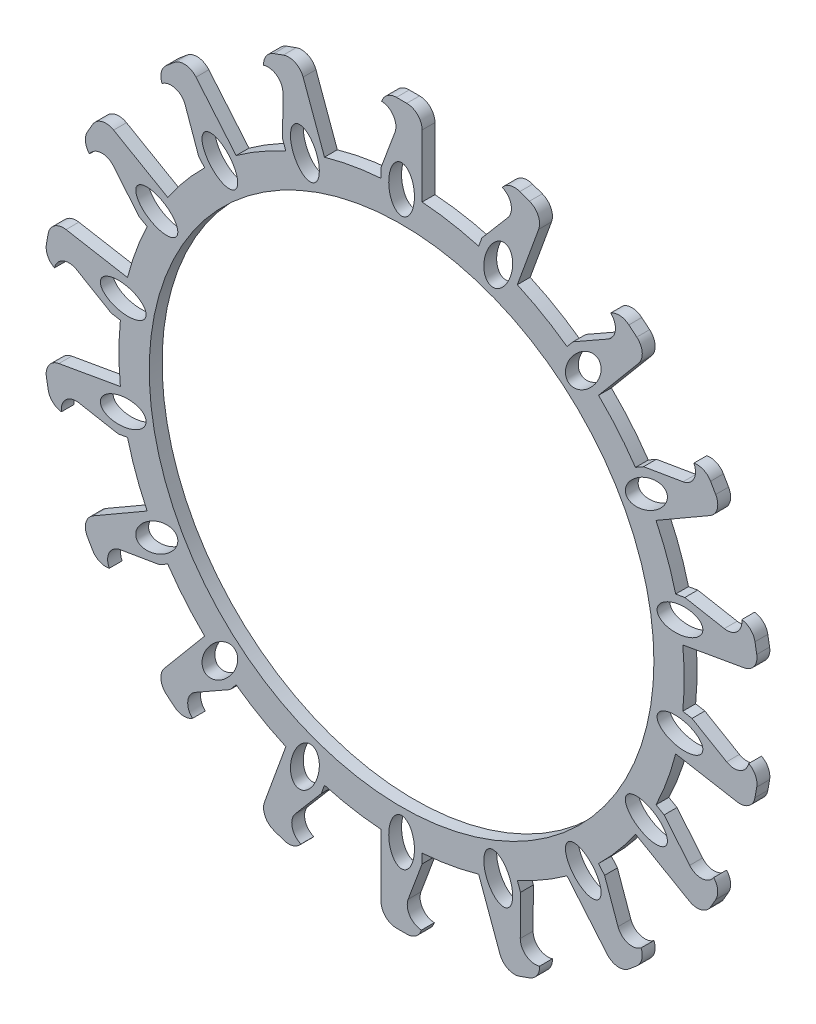
SolidWorks part; units mm, degrees
ref_plane "Front Plane" through (0, 0, 0) normal (0, 0, 1) x (1, 0, 0)
ref_plane "Top Plane" through (0, 0, 0) normal (0, 1, 0) x (1, 0, 0)
ref_plane "Right Plane" through (0, 0, 0) normal (1, 0, 0) x (0, 0, -1)
sketch "Sketch1" plane through (0, 0, 0) normal (0, 0, 1) x (1, 0, 0)
  line L0 (-78.3987, -3.3654) -> (61.3013, -3.3654) construction
  line L1 (-5.8227, 60.5836) -> (-5.8227, 59.1774)
  line L2 (-57.9401, 46.026) -> (40.8427, -52.7569) construction
  line L3 (40.8427, 46.026) -> (-57.9401, -52.7569) construction
  line L4 (-13.4427, 60.5073) -> (-13.4427, 59.1774)
  line L5 (-13.4427, 59.1774) -> (-5.8227, 59.1774)
  line L12 (2.7798, 58.212) -> (10.1401, 56.2398)
  line L13 (10.5041, 57.5981) -> (10.1401, 56.2398)
  line L14 (3.124, 59.4967) -> (2.7798, 58.212)
  line L18 (18.1997, 53.0809) -> (24.7988, 49.2709)
  line L19 (25.5019, 50.4887) -> (24.7988, 49.2709)
  line L20 (18.8647, 54.2327) -> (18.1997, 53.0809)
  line L24 (31.7661, 44.1336) -> (37.1543, 38.7454)
  line L25 (38.1486, 39.7398) -> (37.1543, 38.7454)
  line L26 (32.7065, 45.074) -> (31.7661, 44.1336)
  line L30 (42.5546, 31.9799) -> (46.3646, 25.3808)
  line L31 (47.5824, 26.0839) -> (46.3646, 25.3808)
  line L32 (43.7063, 32.6449) -> (42.5546, 31.9799)
  line L36 (49.8298, 17.4482) -> (51.802, 10.0878)
  line L37 (53.1603, 10.4518) -> (51.802, 10.0878)
  line L38 (51.1145, 17.7924) -> (49.8298, 17.4482)
  line L42 (53.0961, 1.5286) -> (53.0961, -6.0914)
  line L43 (54.5023, -6.0914) -> (53.0961, -6.0914)
  line L44 (54.426, 1.5286) -> (53.0961, 1.5286)
  line L48 (52.1307, -14.6939) -> (50.1585, -22.0543)
  line L49 (51.5168, -22.4183) -> (50.1585, -22.0543)
  line L50 (53.4154, -15.0382) -> (52.1307, -14.6939)
  line L54 (46.9996, -30.1138) -> (43.1896, -36.713)
  line L55 (44.4074, -37.4161) -> (43.1896, -36.713)
  line L56 (48.1513, -30.7788) -> (46.9996, -30.1138)
  line L60 (38.0523, -43.6803) -> (32.6641, -49.0684)
  line L61 (33.6585, -50.0628) -> (32.6641, -49.0684)
  line L62 (38.9927, -44.6207) -> (38.0523, -43.6803)
  line L66 (25.8986, -54.4687) -> (19.2995, -58.2787)
  line L67 (20.0026, -59.4965) -> (19.2995, -58.2787)
  line L68 (26.5636, -55.6205) -> (25.8986, -54.4687)
  line L72 (11.3669, -61.744) -> (4.0065, -63.7162)
  line L73 (4.3705, -65.0745) -> (4.0065, -63.7162)
  line L74 (11.7111, -63.0286) -> (11.3669, -61.744)
  line L78 (-4.5527, -65.0102) -> (-12.1727, -65.0102)
  line L79 (-12.1727, -66.4164) -> (-12.1727, -65.0102)
  line L80 (-4.5527, -66.3402) -> (-4.5527, -65.0102)
  line L84 (-20.7752, -64.0449) -> (-28.1356, -62.0727)
  line L85 (-28.4996, -63.431) -> (-28.1356, -62.0727)
  line L86 (-21.1195, -65.3295) -> (-20.7752, -64.0449)
  line L90 (-36.1951, -58.9137) -> (-42.7943, -55.1037)
  line L91 (-43.4974, -56.3215) -> (-42.7943, -55.1037)
  line L92 (-36.8601, -60.0655) -> (-36.1951, -58.9137)
  line L96 (-49.7616, -49.9665) -> (-55.1497, -44.5783)
  line L97 (-56.1441, -45.5726) -> (-55.1497, -44.5783)
  line L98 (-50.702, -50.9069) -> (-49.7616, -49.9665)
  line L102 (-60.55, -37.8128) -> (-64.36, -31.2137)
  line L103 (-65.5778, -31.9168) -> (-64.36, -31.2137)
  line L104 (-61.7018, -38.4778) -> (-60.55, -37.8128)
  line L109 (-71.1558, -16.2846) -> (-69.7975, -15.9207)
  line L110 (-69.1099, -23.6252) -> (-67.8253, -23.281)
  line L114 (-71.0915, -7.3614) -> (-71.0915, 0.2586)
  line L115 (-72.4977, 0.2586) -> (-71.0915, 0.2586)
  line L116 (-72.4215, -7.3614) -> (-71.0915, -7.3614)
  line L120 (-70.1262, 8.8611) -> (-68.154, 16.2214)
  line L121 (-69.5123, 16.5854) -> (-68.154, 16.2214)
  line L122 (-71.4108, 9.2053) -> (-70.1262, 8.8611)
  line L126 (-64.995, 24.281) -> (-61.185, 30.8801)
  line L127 (-62.4028, 31.5832) -> (-61.185, 30.8801)
  line L128 (-66.1468, 24.946) -> (-64.995, 24.281)
  line L132 (-56.0478, 37.8474) -> (-50.6596, 43.2356)
  line L133 (-51.6539, 44.2299) -> (-50.6596, 43.2356)
  line L134 (-56.9882, 38.7878) -> (-56.0478, 37.8474)
  line L138 (-43.8941, 48.6359) -> (-37.295, 52.4459)
  line L139 (-37.9981, 53.6637) -> (-37.295, 52.4459)
  line L140 (-44.5591, 49.7877) -> (-43.8941, 48.6359)
  line L144 (-29.3623, 55.9111) -> (-22.002, 57.8833)
  line L145 (-22.3659, 59.2416) -> (-22.002, 57.8833)
  line L146 (-29.7065, 57.1958) -> (-29.3623, 55.9111)
  line L147 (-8.9977, -2.9164) -> (-5.8227, 59.1774) construction
  line L148 (-8.9977, -2.9164) -> (10.1401, 56.2398) construction
  line L170 (-67.8253, -23.281) -> (-69.7975, -15.9207) [skipped]
  circle A0 centre (-8.5487, -3.3654) radius 55.245
  circle A1 centre (-8.5487, -3.3654) radius 69.85
  dimension "D1" = 110.49
  dimension "D2" = 139.7
  dimension "D4" = 7.62
  dimension "D5" = 24
  dimension "D6" = 15
extrude "Boss-Extrude1" add sketch "Sketch1" along normal blind 3.175
sketch "Sketch2" plane through (0, 0, 3.175) normal (0, 0, -1) x (-1, 0, 0)
  line L0 (8.5487, 66.4846) -> (8.5487, -73.2154) construction
  line L1 (8.5487, 62.6746) -> (13.6287, 62.6746)
  line L2 (8.5487, 62.6746) -> (3.4687, 62.6746)
  line L3 (3.4687, 62.6746) -> (3.4687, 85.5346)
  line L4 (3.4687, 85.5346) -> (13.6287, 85.5346)
  line L5 (13.6287, 85.5346) -> (13.6287, 62.6746)
  line L6 (8.5487, -3.3654) -> (-61.3013, -3.3654) construction
  line L7 (34.1807, 81.9107) -> (43.7279, 78.4358)
  line L8 (43.7279, 78.4358) -> (35.9094, 56.9544)
  line L9 (26.3621, 60.4293) -> (34.1807, 81.9107)
  line L10 (31.1357, 58.6919) -> (26.3621, 60.4293)
  line L11 (31.1357, 58.6919) -> (35.9094, 56.9544)
  line L12 (61.801, 68.0013) -> (69.584, 61.4705)
  line L13 (69.584, 61.4705) -> (54.8899, 43.9588)
  line L14 (47.1069, 50.4895) -> (61.801, 68.0013)
  line L15 (50.9984, 47.2241) -> (47.1069, 50.4895)
  line L16 (50.9984, 47.2241) -> (54.8899, 43.9588)
  line L17 (82.9984, 45.484) -> (88.0784, 36.6851)
  line L18 (88.0784, 36.6851) -> (68.281, 25.2551)
  line L19 (63.201, 34.054) -> (82.9984, 45.484)
  line L20 (65.741, 29.6546) -> (63.201, 34.054)
  line L21 (65.741, 29.6546) -> (68.281, 25.2551)
  line L22 (95.216, 17.0747) -> (96.9803, 7.0691)
  line L23 (96.9803, 7.0691) -> (74.4676, 3.0995)
  line L24 (72.7033, 13.1051) -> (95.216, 17.0747)
  line L25 (73.5854, 8.1023) -> (72.7033, 13.1051)
  line L26 (73.5854, 8.1023) -> (74.4676, 3.0995)
  line L27 (96.9803, -13.7999) -> (95.216, -23.8056)
  line L28 (95.216, -23.8056) -> (72.7033, -19.836)
  line L29 (74.4676, -9.8303) -> (96.9803, -13.7999)
  line L30 (73.5854, -14.8332) -> (74.4676, -9.8303)
  line L31 (73.5854, -14.8332) -> (72.7033, -19.836)
  line L32 (88.0784, -43.416) -> (82.9984, -52.2149)
  line L33 (82.9984, -52.2149) -> (63.201, -40.7849)
  line L34 (68.281, -31.986) -> (88.0784, -43.416)
  line L35 (65.741, -36.3854) -> (68.281, -31.986)
  line L36 (65.741, -36.3854) -> (63.201, -40.7849)
  line L37 (69.584, -68.2014) -> (61.801, -74.7322)
  line L38 (61.801, -74.7322) -> (47.1069, -57.2204)
  line L39 (54.8899, -50.6897) -> (69.584, -68.2014)
  line L40 (50.9984, -53.955) -> (54.8899, -50.6897)
  line L41 (50.9984, -53.955) -> (47.1069, -57.2204)
  line L42 (43.7279, -85.1667) -> (34.1807, -88.6416)
  line L43 (34.1807, -88.6416) -> (26.3621, -67.1602)
  line L44 (35.9094, -63.6853) -> (43.7279, -85.1667)
  line L45 (31.1357, -65.4227) -> (35.9094, -63.6853)
  line L46 (31.1357, -65.4227) -> (26.3621, -67.1602)
  line L47 (13.6287, -92.2654) -> (3.4687, -92.2654)
  line L48 (3.4687, -92.2654) -> (3.4687, -69.4054)
  line L49 (13.6287, -69.4054) -> (13.6287, -92.2654)
  line L50 (8.5487, -69.4054) -> (13.6287, -69.4054)
  line L51 (8.5487, -69.4054) -> (3.4687, -69.4054)
  line L52 (-17.0832, -88.6416) -> (-26.6305, -85.1667)
  line L53 (-26.6305, -85.1667) -> (-18.8119, -63.6853)
  line L54 (-9.2647, -67.1602) -> (-17.0832, -88.6416)
  line L55 (-14.0383, -65.4227) -> (-9.2647, -67.1602)
  line L56 (-14.0383, -65.4227) -> (-18.8119, -63.6853)
  line L57 (-44.7036, -74.7322) -> (-52.4866, -68.2014)
  line L58 (-52.4866, -68.2014) -> (-37.7925, -50.6897)
  line L59 (-30.0095, -57.2204) -> (-44.7036, -74.7322)
  line L60 (-33.901, -53.955) -> (-30.0095, -57.2204)
  line L61 (-33.901, -53.955) -> (-37.7925, -50.6897)
  line L62 (-65.9009, -52.2149) -> (-70.9809, -43.416)
  line L63 (-70.9809, -43.416) -> (-51.1836, -31.986)
  line L64 (-46.1036, -40.7849) -> (-65.9009, -52.2149)
  line L65 (-48.6436, -36.3854) -> (-46.1036, -40.7849)
  line L66 (-48.6436, -36.3854) -> (-51.1836, -31.986)
  line L67 (-78.1186, -23.8056) -> (-79.8828, -13.7999)
  line L68 (-79.8828, -13.7999) -> (-57.3701, -9.8303)
  line L69 (-55.6059, -19.836) -> (-78.1186, -23.8056)
  line L70 (-56.488, -14.8332) -> (-55.6059, -19.836)
  line L71 (-56.488, -14.8332) -> (-57.3701, -9.8303)
  line L72 (-79.8828, 7.0691) -> (-78.1186, 17.0747)
  line L73 (-78.1186, 17.0747) -> (-55.6059, 13.1051)
  line L74 (-57.3701, 3.0995) -> (-79.8828, 7.0691)
  line L75 (-56.488, 8.1023) -> (-57.3701, 3.0995)
  line L76 (-56.488, 8.1023) -> (-55.6059, 13.1051)
  line L77 (-70.9809, 36.6851) -> (-65.9009, 45.484)
  line L78 (-65.9009, 45.484) -> (-46.1036, 34.054)
  line L79 (-51.1836, 25.2551) -> (-70.9809, 36.6851)
  line L80 (-48.6436, 29.6546) -> (-51.1836, 25.2551)
  line L81 (-48.6436, 29.6546) -> (-46.1036, 34.054)
  line L82 (-52.4866, 61.4705) -> (-44.7036, 68.0013)
  line L83 (-44.7036, 68.0013) -> (-30.0095, 50.4895)
  line L84 (-37.7925, 43.9588) -> (-52.4866, 61.4705)
  line L85 (-33.901, 47.2241) -> (-37.7925, 43.9588)
  line L86 (-33.901, 47.2241) -> (-30.0095, 50.4895)
  line L87 (-26.6305, 78.4358) -> (-17.0832, 81.9107)
  line L88 (-17.0832, 81.9107) -> (-9.2647, 60.4293)
  line L89 (-18.8119, 56.9544) -> (-26.6305, 78.4358)
  line L90 (-14.0383, 58.6919) -> (-18.8119, 56.9544)
  line L91 (-14.0383, 58.6919) -> (-9.2647, 60.4293)
  circle A2 centre (8.5487, -3.3654) radius 69.85 construction
  point P99 (8.5487, -3.3654)
  dimension "D3" = 3.81
  dimension "D1" = 5.08
  dimension "D2" = 5.08
  dimension "D4" = 22.86
  dimension "D5" = 18
extrude "Boss-Extrude2" add sketch "Sketch2" along normal blind 3.175
fillet "Fillet4" radius 3.81 36 edges at (-13.6287, 85.5346, 1.5875) (-3.4687, 85.5346, 1.5875) (-88.0784, 36.6851, 1.5875) (-82.9984, 45.484, 1.5875) (-95.216, 17.0747, 1.5875) (-96.9803, 7.0691, 1.5875) (-96.9803, -13.7999, 1.5875) (-95.216, -23.8056, 1.5875) (-88.0784, -43.416, 1.5875) (-82.9984, -52.2149, 1.5875) (-69.584, -68.2014, 1.5875) (-61.801, -74.7322, 1.5875) (-43.7279, -85.1667, 1.5875) (-34.1807, -88.6416, 1.5875) (-13.6287, -92.2654, 1.5875) (-3.4687, -92.2654, 1.5875) (17.0832, -88.6416, 1.5875) (26.6305, -85.1667, 1.5875) (52.4866, -68.2014, 1.5875) (44.7036, -74.7322, 1.5875) (65.9009, -52.2149, 1.5875) (70.9809, -43.416, 1.5875) (78.1186, -23.8056, 1.5875) (79.8828, -13.7999, 1.5875) (79.8828, 7.0691, 1.5875) (78.1186, 17.0747, 1.5875) (70.9809, 36.6851, 1.5875) (65.9009, 45.484, 1.5875) (52.4866, 61.4705, 1.5875) (44.7036, 68.0013, 1.5875) (26.6305, 78.4358, 1.5875) (17.0832, 81.9107, 1.5875) (-69.584, 61.4705, 1.5875) (-61.801, 68.0013, 1.5875) (-43.7279, 78.4358, 1.5875) (-34.1807, 81.9107, 1.5875)
sketch "Sketch3" plane through (0, 0, 0) normal (0, 0, -1) x (-1, 0, 0)
  line L0 (17.0808, 69.8995) -> (13.6287, 79.1846) construction
  line L1 (13.6287, 66.2996) -> (13.6287, 81.7246) construction
  line L2 (13.6287, 68.616) -> (10.1766, 77.9011)
  line L3 (20.533, 71.183) -> (17.0808, 80.468)
  line L4 (13.6287, 66.2996) -> (13.6287, 81.7246) construction
  line L5 (8.5487, 51.8796) -> (8.5487, -58.6104) construction
  line L6 (-46.6963, -3.3654) -> (63.7937, -3.3654) construction
  line L7 (41.6244, 62.563) -> (41.5561, 72.4687) construction
  line L8 (37.9415, 62.5376) -> (37.8732, 72.4433)
  line L9 (45.3073, 62.5883) -> (45.239, 72.4941)
  line L10 (62.1785, 47.2744) -> (65.5023, 56.6062) construction
  line L11 (58.709, 48.5102) -> (62.0329, 57.8419)
  line L12 (65.648, 46.0387) -> (68.9718, 55.3704)
  line L13 (76.2641, 25.878) -> (82.5791, 33.5101) construction
  line L14 (73.4265, 28.2259) -> (79.7415, 35.858)
  line L15 (79.1017, 23.5301) -> (85.4167, 31.1623)
  line L16 (82.1822, 0.9544) -> (90.7267, 5.9664) construction
  line L17 (80.3188, 4.1312) -> (88.8633, 9.1432)
  line L18 (84.0457, -2.2224) -> (92.5902, 2.7896)
  line L19 (79.219, -24.4903) -> (88.9625, -22.7029) construction
  line L20 (78.5545, -20.8677) -> (88.2979, -19.0804)
  line L21 (79.8836, -28.1128) -> (89.627, -26.3255)
  line L22 (67.732, -47.387) -> (77.4991, -49.0399) construction
  line L23 (68.3465, -43.7556) -> (78.1137, -45.4085)
  line L24 (67.1175, -51.0183) -> (76.8846, -52.6712)
  line L25 (49.1066, -64.974) -> (57.7193, -69.8678) construction
  line L26 (50.926, -61.7718) -> (59.5388, -66.6656)
  line L27 (47.2871, -68.1762) -> (55.8999, -73.07)
  line L28 (25.5892, -75.1302) -> (32.0088, -82.6745) construction
  line L29 (28.3942, -72.7434) -> (34.8138, -80.2878)
  line L30 (22.7843, -77.5169) -> (29.2039, -85.0613)
  line L31 (0.0166, -76.6304) -> (3.4687, -85.9154) construction
  line L32 (3.4687, -75.3469) -> (6.9208, -84.632)
  line L33 (-3.4355, -77.9139) -> (0.0166, -87.1989)
  line L34 (-24.527, -69.2938) -> (-24.4587, -79.1996) construction
  line L35 (-20.844, -69.2685) -> (-20.7758, -79.1742)
  line L36 (-28.2099, -69.3192) -> (-28.1416, -79.225)
  line L37 (-45.0811, -54.0053) -> (-48.4049, -63.3371) construction
  line L38 (-41.6116, -55.2411) -> (-44.9354, -64.5728)
  line L39 (-48.5506, -52.7695) -> (-51.8744, -62.1013)
  line L40 (-59.1667, -32.6089) -> (-65.4817, -40.241) construction
  line L41 (-56.3291, -34.9568) -> (-62.6441, -42.5889)
  line L42 (-62.0043, -30.261) -> (-68.3193, -37.8931)
  line L43 (-65.0848, -7.6853) -> (-73.6293, -12.6973) construction
  line L44 (-63.2213, -10.8621) -> (-71.7659, -15.8741)
  line L45 (-66.9482, -4.5085) -> (-75.4927, -9.5205)
  line L46 (-62.1216, 17.7594) -> (-71.865, 15.972) construction
  line L47 (-61.4571, 14.1368) -> (-71.2005, 12.3495)
  line L48 (-62.7861, 21.3819) -> (-72.5296, 19.5946)
  line L49 (-50.6345, 40.6561) -> (-60.4017, 42.309) construction
  line L50 (-51.2491, 37.0247) -> (-61.0162, 38.6776)
  line L51 (-50.02, 44.2874) -> (-59.7871, 45.9403)
  line L52 (-32.0091, 58.2431) -> (-40.6219, 63.1369) construction
  line L53 (-33.8286, 55.0409) -> (-42.4414, 59.9347)
  line L54 (-30.1896, 61.4453) -> (-38.8024, 66.3391)
  line L55 (-8.4918, 68.3993) -> (-14.9114, 75.9436) construction
  line L56 (-11.2968, 66.0125) -> (-17.7164, 73.5569)
  line L57 (-5.6868, 70.786) -> (-12.1064, 78.3304)
  line L58 (8.5487, -3.3654) -> (17.0808, 69.8995) construction
  arc A0 (13.6287, 68.616) -> (20.533, 71.183) centre (17.0808, 69.8995) ccw
  arc A1 (17.0808, 80.468) -> (10.1766, 77.9011) centre (13.6287, 79.1846) ccw
  circle A2 centre (8.5487, -3.3654) radius 55.245 construction
  arc A3 (37.9415, 62.5376) -> (45.3073, 62.5883) centre (41.6244, 62.563) ccw
  arc A4 (45.239, 72.4941) -> (37.8732, 72.4433) centre (41.5561, 72.4687) ccw
  arc A5 (58.709, 48.5102) -> (65.648, 46.0387) centre (62.1785, 47.2744) ccw
  arc A6 (68.9718, 55.3704) -> (62.0329, 57.8419) centre (65.5023, 56.6062) ccw
  arc A7 (73.4265, 28.2259) -> (79.1017, 23.5301) centre (76.2641, 25.878) ccw
  arc A8 (85.4167, 31.1623) -> (79.7415, 35.858) centre (82.5791, 33.5101) ccw
  arc A9 (80.3188, 4.1312) -> (84.0457, -2.2224) centre (82.1822, 0.9544) ccw
  arc A10 (92.5902, 2.7896) -> (88.8633, 9.1432) centre (90.7267, 5.9664) ccw
  arc A11 (78.5545, -20.8677) -> (79.8836, -28.1128) centre (79.219, -24.4903) ccw
  arc A12 (89.627, -26.3255) -> (88.2979, -19.0804) centre (88.9625, -22.7029) ccw
  arc A13 (68.3465, -43.7556) -> (67.1175, -51.0183) centre (67.732, -47.387) ccw
  arc A14 (76.8846, -52.6712) -> (78.1137, -45.4085) centre (77.4991, -49.0399) ccw
  arc A15 (50.926, -61.7718) -> (47.2871, -68.1762) centre (49.1066, -64.974) ccw
  arc A16 (55.8999, -73.07) -> (59.5388, -66.6656) centre (57.7193, -69.8678) ccw
  arc A17 (28.3942, -72.7434) -> (22.7843, -77.5169) centre (25.5892, -75.1302) ccw
  arc A18 (29.2039, -85.0613) -> (34.8138, -80.2878) centre (32.0088, -82.6745) ccw
  arc A19 (3.4687, -75.3469) -> (-3.4355, -77.9139) centre (0.0166, -76.6304) ccw
  arc A20 (0.0166, -87.1989) -> (6.9208, -84.632) centre (3.4687, -85.9154) ccw
  arc A21 (-20.844, -69.2685) -> (-28.2099, -69.3192) centre (-24.527, -69.2938) ccw
  arc A22 (-28.1416, -79.225) -> (-20.7758, -79.1742) centre (-24.4587, -79.1996) ccw
  arc A23 (-41.6116, -55.2411) -> (-48.5506, -52.7695) centre (-45.0811, -54.0053) ccw
  arc A24 (-51.8744, -62.1013) -> (-44.9354, -64.5728) centre (-48.4049, -63.3371) ccw
  arc A25 (-56.3291, -34.9568) -> (-62.0043, -30.261) centre (-59.1667, -32.6089) ccw
  arc A26 (-68.3193, -37.8931) -> (-62.6441, -42.5889) centre (-65.4817, -40.241) ccw
  arc A27 (-63.2213, -10.8621) -> (-66.9482, -4.5085) centre (-65.0848, -7.6853) ccw
  arc A28 (-75.4927, -9.5205) -> (-71.7659, -15.8741) centre (-73.6293, -12.6973) ccw
  arc A29 (-61.4571, 14.1368) -> (-62.7861, 21.3819) centre (-62.1216, 17.7594) ccw
  arc A30 (-72.5296, 19.5946) -> (-71.2005, 12.3495) centre (-71.865, 15.972) ccw
  arc A31 (-51.2491, 37.0247) -> (-50.02, 44.2874) centre (-50.6345, 40.6561) ccw
  arc A32 (-59.7871, 45.9403) -> (-61.0162, 38.6776) centre (-60.4017, 42.309) ccw
  arc A33 (-33.8286, 55.0409) -> (-30.1896, 61.4453) centre (-32.0091, 58.2431) ccw
  arc A34 (-38.8024, 66.3391) -> (-42.4414, 59.9347) centre (-40.6219, 63.1369) ccw
  arc A35 (-11.2968, 66.0125) -> (-5.6868, 70.786) centre (-8.4918, 68.3993) ccw
  arc A36 (-12.1064, 78.3304) -> (-17.7164, 73.5569) centre (-14.9114, 75.9436) ccw
  point P4 (15.3548, 74.542)
  point P10 (9.1837, -3.8983)
  point P11 (9.1837, -3.8983)
  point P21 (41.5903, 67.5158)
  point P28 (63.8404, 51.9403)
  point P35 (79.4216, 29.6941)
  point P42 (86.4545, 3.4604)
  point P49 (84.0908, -23.5966)
  point P56 (72.6156, -48.2134)
  point P63 (53.4129, -67.4209)
  point P70 (28.799, -78.9023)
  point P77 (1.7427, -81.2729)
  point P84 (-24.4928, -74.2467)
  point P91 (-46.743, -58.6712)
  point P98 (-62.3242, -36.425)
  point P105 (-69.357, -10.1913)
  point P112 (-66.9933, 16.8657)
  point P119 (-55.5181, 41.4825)
  point P126 (-36.3155, 60.69)
  point P131 (9.1837, -3.8983)
  point P133 (9.1837, -3.8983)
  point P134 (9.1837, -3.8983)
  point P135 (9.1837, -3.8983)
  point P136 (9.1837, -3.8983)
  point P137 (9.1837, -3.8983)
  point P138 (9.1837, -3.8983)
  point P139 (9.1837, -3.8983)
  point P140 (9.1837, -3.8983)
  point P141 (9.1837, -3.8983)
  point P142 (9.1837, -3.8983)
  point P143 (9.1837, -3.8983)
  point P144 (9.1837, -3.8983)
  point P145 (9.1837, -3.8983)
  point P146 (9.1837, -3.8983)
  point P152 (-11.7016, 72.1715)
  dimension "D1" = 7.366
  dimension "D2" = 6.35
  dimension "D3" = 9.906
  dimension "D4" = 18
  dimension "D5" = 73.7601
extrude "Cut-Extrude1" cut sketch "Sketch3" against normal through all
sketch "Sketch4" plane through (0, 0, 0) normal (0, 0, -1) x (-1, 0, 0)
  line L0 (3.4687, 81.7246) -> (3.4687, 66.2996) construction
  arc A0 (3.4687, 66.2996) -> (-10.5045, 63.8357) centre (8.5487, -3.3654) ccw construction
  ellipse E0 centre (8.5487, 66.4846) end of major axis (8.5487, 72.1996) minor radius 3.175
  dimension "D1" = 5.08
  dimension "D2" = 6.35
  dimension "D3" = 11.43
extrude "Cut-Extrude2" cut sketch "Sketch4" against normal through all
pattern_circular "CirPattern2" count 18 over 360 about axis through (-8.5487, -3.3654, 0) along (0, 0, 1) of "Cut-Extrude2"
sketch "Sketch5" plane through (0, 0, 3.175) normal (0, 0, 1) x (1, 0, 0)
  line L0 (-8.5487, 51.8796) -> (-8.5487, -58.6104) construction
  line L1 (-63.7937, -3.3654) -> (46.6963, -3.3654) construction
  circle A0 centre (-8.5487, -3.3654) radius 55.245 construction
  circle A1 centre (-8.5487, -3.3654) radius 62.357
  dimension "D1" = 124.714
extrude "Cut-Extrude5" cut sketch "Sketch5" against normal through all
